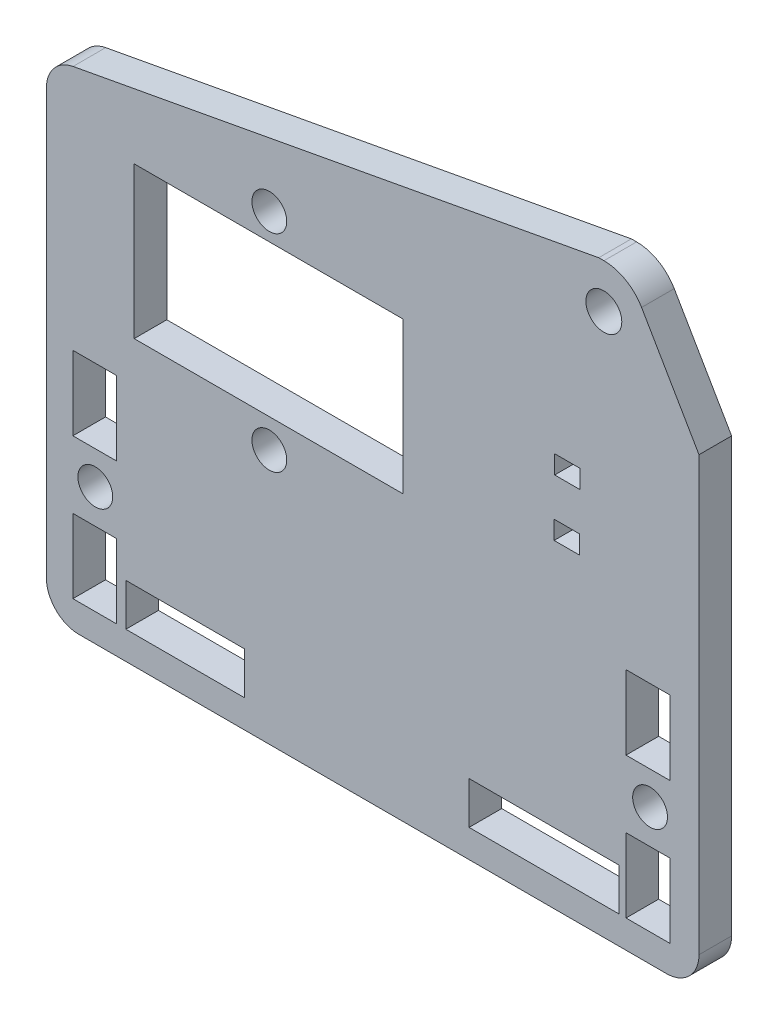
SolidWorks part; units mm, degrees
ref_plane "前视基准面" through (0, 0, 0) normal (0, 0, 1) x (1, 0, 0)
ref_plane "上视基准面" through (0, 0, 0) normal (0, 1, 0) x (1, 0, 0)
ref_plane "右视基准面" through (0, 0, 0) normal (1, 0, 0) x (0, 0, -1)
ref_plane "基准面4" through (0, 0, 0) normal (0, 0, -1) x (-1, 0, 0)
sketch "草图1" plane through (0, 0, 0) normal (0, 0, -1) x (-1, 0, 0)
  line L0 (-2.4385, -12.4286) -> (-6.4349, -12.4286)
  line L1 (-6.4349, -12.4286) -> (-6.4349, -5.6222)
  line L2 (-6.4349, -5.6222) -> (-2.4385, -5.6222)
  line L3 (-2.4385, -5.6222) -> (-2.4385, -12.4286)
  line L4 (-56.997, -27.963) -> (-2.9998, -27.963)
  line L5 (0, -24.9631) -> (0, 14.0348)
  line L6 (-2.4544, 16.9847) -> (-50.78, 25.9199)
  line L7 (-50.78, 25.9199) -> (-51.2601, 25.9199)
  line L8 (-54.7186, 23.9294) -> (-59.9968, 14.8437)
  line L9 (-59.9968, 14.8437) -> (-59.9968, -24.9631)
  line L10 (-2.4385, -18.605) -> (-2.4385, -25.3957)
  line L11 (-2.4385, -25.3957) -> (-6.4349, -25.3957)
  line L12 (-6.4349, -25.3957) -> (-6.4349, -18.605)
  line L13 (-6.4349, -18.605) -> (-2.4385, -18.605)
  line L14 (-53.2864, -18.605) -> (-53.2864, -25.3957)
  line L15 (-53.2864, -25.3957) -> (-57.3185, -25.3957)
  line L16 (-57.3185, -25.3957) -> (-57.3185, -18.605)
  line L17 (-57.3185, -18.605) -> (-53.2864, -18.605)
  line L18 (-53.2864, -5.6222) -> (-53.2864, -12.4286)
  line L19 (-53.2864, -12.4286) -> (-57.3185, -12.4286)
  line L20 (-57.3185, -12.4286) -> (-57.3185, -5.6222)
  line L21 (-57.3185, -5.6222) -> (-53.2864, -5.6222)
  line L22 (-7.3078, -21.5037) -> (-7.3078, -25.3957)
  line L23 (-7.3078, -25.3957) -> (-18.2358, -25.3957)
  line L24 (-18.2358, -25.3957) -> (-18.2358, -21.5037)
  line L25 (-18.2358, -21.5037) -> (-7.3078, -21.5037)
  line L26 (-38.8595, -21.5037) -> (-38.8595, -25.3957)
  line L27 (-38.8595, -25.3957) -> (-52.6623, -25.3957)
  line L28 (-52.6623, -25.3957) -> (-52.6623, -21.5037)
  line L29 (-52.6623, -21.5037) -> (-38.8595, -21.5037)
  line L30 (-46.7285, 8.2902) -> (-46.7285, 6.5973)
  line L31 (-46.7285, 6.5973) -> (-49.0574, 6.5973)
  line L32 (-49.0574, 6.5973) -> (-49.0574, 8.2902)
  line L33 (-49.0574, 8.2902) -> (-46.7285, 8.2902)
  line L34 (-46.6765, 3.0515) -> (-46.6765, 1.3586)
  line L35 (-46.6765, 1.3586) -> (-49.0054, 1.3586)
  line L36 (-49.0054, 1.3586) -> (-49.0054, 3.0515)
  line L37 (-49.0054, 3.0515) -> (-46.6765, 3.0515)
  line L38 (-8.0714, 12.0403) -> (-8.0714, -1.8754)
  line L39 (-8.0714, -1.8754) -> (-32.7719, -1.8754)
  line L40 (-32.7719, -1.8754) -> (-32.7719, 12.0403)
  line L41 (-32.7719, 12.0403) -> (-8.0714, 12.0403)
  arc A0 (-59.9968, -24.9631) -> (-56.997, -27.963) centre (-56.997, -24.9631) ccw
  arc A1 (-2.9998, -27.963) -> (0, -24.9631) centre (-2.9998, -24.9631) ccw
  arc A2 (0, 14.0348) -> (-2.4544, 16.9847) centre (-2.9998, 14.0348) ccw
  arc A3 (-51.2601, 25.9199) -> (-54.7186, 23.9294) centre (-51.2601, 21.9202) ccw
  circle A4 centre (-55.4971, -15.4635) radius 1.3589
  circle A5 centre (-4.4998, -15.4635) radius 1.3589
  circle A6 centre (-20.4979, -4.5351) radius 1.5999
  circle A7 centre (-20.4979, 14.4649) radius 1.5999
  circle A8 centre (-51.2483, 21.8685) radius 1.6499
  dimension "D1" = 19
extrude "凸台-拉伸1" add sketch "草图1" against normal blind 3
sketch "草图2" plane through (0, 0, 3) normal (0, 0, 1) x (1, 0, 0)
  circle A0 centre (55.4971, -15.4635) radius 1.6
  circle A1 centre (4.4998, -15.4635) radius 1.6
  dimension "D1" = 3.2
extrude "切除-拉伸1" cut sketch "草图2" against normal through all
